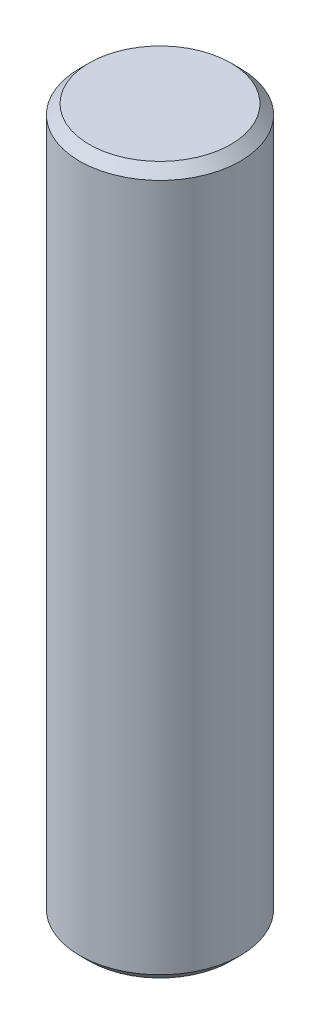
SolidWorks part; units mm, degrees
material "1.7131 (16MnCr5)"
ref_plane "Front Plane" through (0, 0, 0) normal (0, 0, 1) x (1, 0, 0)
ref_plane "Top Plane" through (0, 0, 0) normal (0, 1, 0) x (1, 0, 0)
ref_plane "Right Plane" through (0, 0, 0) normal (1, 0, 0) x (0, 0, -1)
sketch "Sketch1" plane through (0, 0, 0) normal (0, 1, 0) x (1, 0, 0)
  circle A0 centre (0, 0) radius 25
  dimension "D1" = 50
extrude "Boss-Extrude1" add sketch "Sketch1" against normal blind 220
chamfer "Chamfer1" distance 3 angle 45 2 edges at (0, -220, 25) (0, 0, 25)
